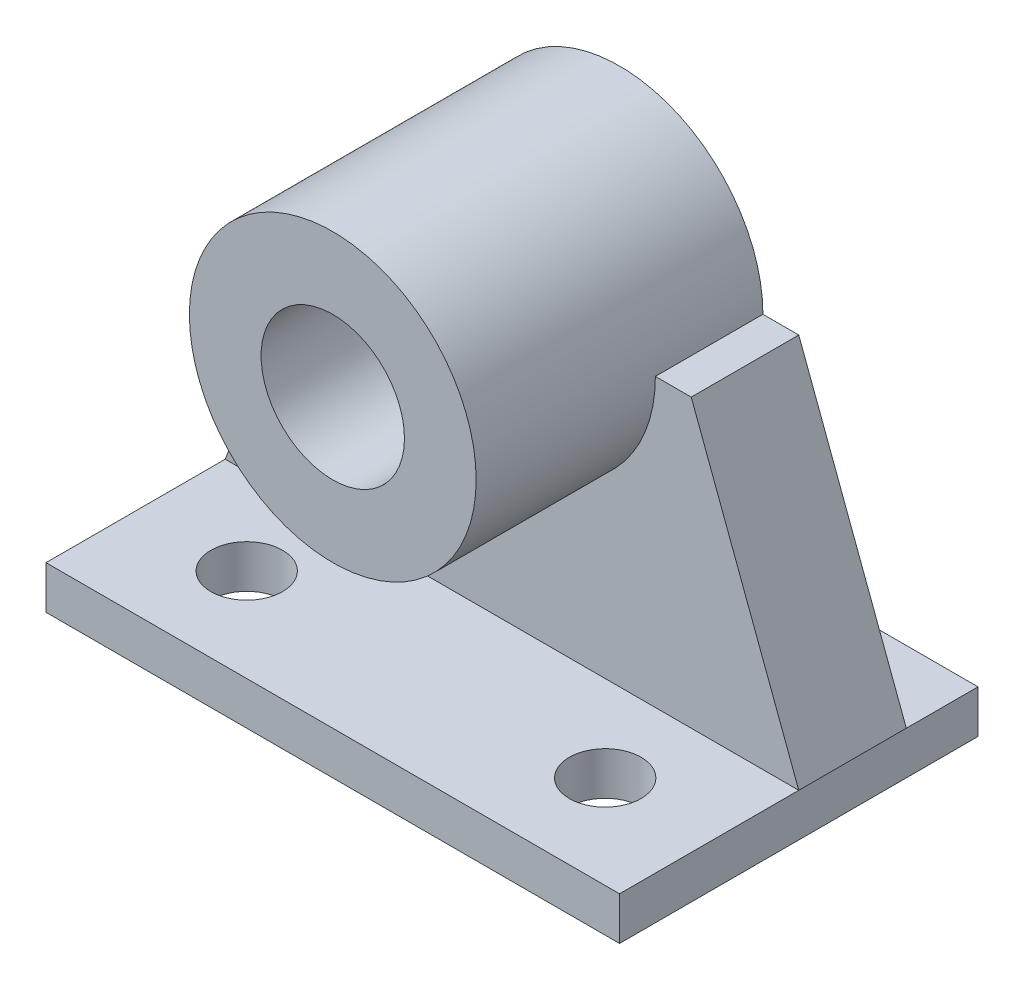
SolidWorks part; units mm, degrees
ref_plane "Front Plane" through (0, 0, 0) normal (0, 0, 1) x (1, 0, 0)
ref_plane "Top Plane" through (0, 0, 0) normal (0, 1, 0) x (1, 0, 0)
ref_plane "Right Plane" through (0, 0, 0) normal (1, 0, 0) x (0, 0, -1)
sketch "Sketch1" plane through (0, 0, 0) normal (0, 0, 1) x (1, 0, 0)
  line L0 (-38.0856, 0) -> (41.9144, 0)
  line L1 (41.9144, 0) -> (41.9144, -6)
  line L2 (41.9144, -6) -> (-38.0856, -6)
  line L3 (-38.0856, -6) -> (-38.0856, 0)
  dimension "D1" = 80
  dimension "D2" = 6
extrude "Boss-Extrude1" add sketch "Sketch1" against normal blind 50
move or copy body "Body-Move/Copy2" bodies to move or copy 101 copy no translate (0, 0, 25) parameters "D1"=0, "D2"=0, "D3"=25
sketch "Sketch6" plane through (0, 0, 0) normal (0, 0, 1) x (1, 0, 0)
  line L0 (41.9144, 0) -> (26.9144, 40)
  line L1 (41.9144, 0) -> (-38.0856, 0)
  line L2 (-38.0856, 0) -> (-23.0856, 40)
  line L3 (-23.0856, 40) -> (-18.0856, 40)
  line L4 (21.9144, 40) -> (26.9144, 40)
  circle A0 centre (1.9144, 40) radius 20
  dimension "D3" = 50
extrude "Boss-Extrude2" add sketch "Sketch6" against normal blind 15 contours A0 L3 L2 L1 L0 L4 | A0
sketch "Sketch7" plane through (0, 0, 0) normal (0, 0, 1) x (1, 0, 0)
  circle A0 centre (1.9144, 40) radius 20
extrude "Boss-Extrude3" add sketch "Sketch7" along normal blind 25
sketch "Sketch8" plane through (0, 0, 25) normal (0, 0, 1) x (1, 0, 0)
  circle A0 centre (1.9144, 40) radius 10
extrude "Cut-Extrude1" cut sketch "Sketch8" against normal up to next
sketch "Sketch9" plane through (0, 0, 0) normal (0, 1, 0) x (1, 0, 0)
  line L0 (26.9144, -7) -> (26.9144, -17) construction
  line L1 (-23.0856, -7) -> (-23.0856, -17) construction
  line L2 (41.9144, 0) -> (41.9144, -25) construction
  line L3 (-38.0856, 0) -> (-38.0856, -25) construction
  line L4 (-28.0856, -12) -> (-18.0856, -12) construction
  line L5 (21.9144, -12) -> (31.9144, -12) construction
  line L6 (41.9144, -25) -> (-38.0856, -25) construction
  circle A0 centre (26.9144, -12) radius 5
  circle A1 centre (-23.0856, -12) radius 5
  dimension "D1" = 15
  dimension "D2" = 15
  dimension "D3" = 13
  dimension "D4" = 13
extrude "Cut-Extrude2" cut sketch "Sketch9" against normal up to next contours A1 | A0
